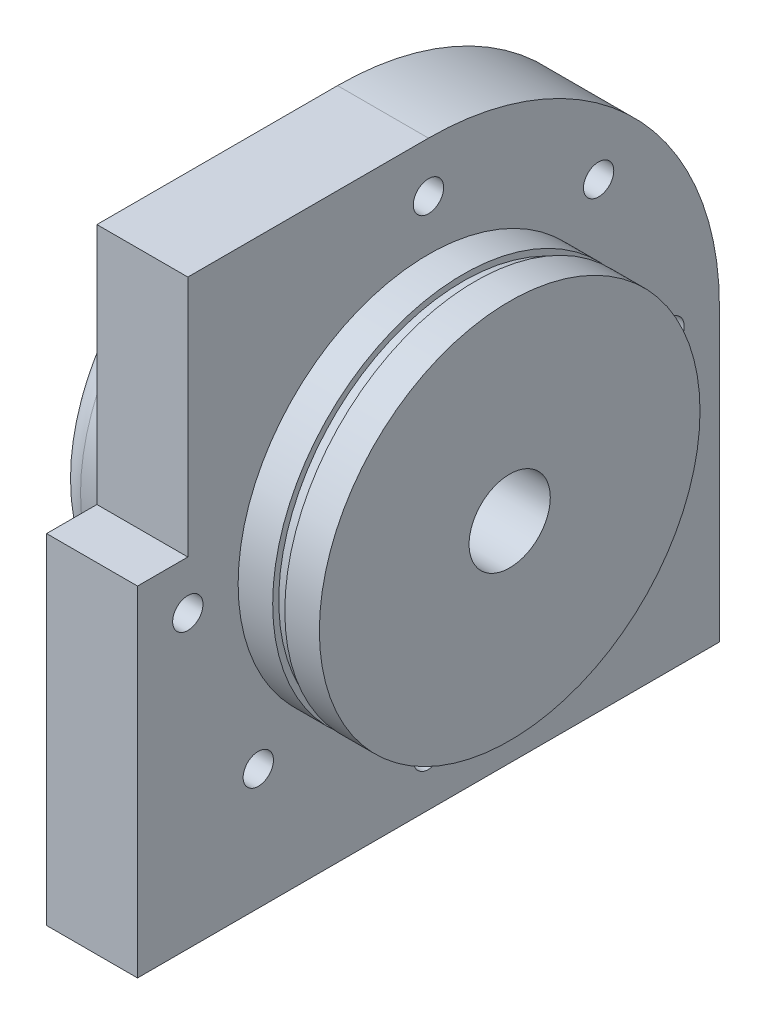
SolidWorks part; units mm, degrees
ref_plane "Front Plane" through (0, 0, 0) normal (0, 0, 1) x (1, 0, 0)
ref_plane "Top Plane" through (0, 0, 0) normal (0, 1, 0) x (1, 0, 0)
ref_plane "Right Plane" through (0, 0, 0) normal (1, 0, 0) x (0, 0, -1)
sketch "Sketch1" plane through (0, 0, 0) normal (1, 0, 0) x (0, 0, -1)
  circle A0 centre (0, 0) radius 39.878
extrude "Housing Fitting Extrude" add sketch "Sketch1" along normal blind 17.018
sketch "Sketch2" plane through (0, 0, 0) normal (-1, 0, 0) x (0, 0, 1)
  line L0 (60.96, 0) -> (60.96, 60.96)
  line L1 (60.96, 60.96) -> (0, 60.96)
  line L2 (60.96, 0) -> (60.96, -54.61)
  line L3 (60.96, -60.96) -> (-60.96, -60.96)
  line L7 (0, -9.3599) -> (0, 9.3599) construction
  line L11 (-60.96, 0) -> (-60.96, -54.61)
  line L12 (60.96, -60.96) -> (60.96, -54.61)
  line L13 (-60.96, -60.96) -> (-60.96, -54.61)
  arc A0 (0, 60.96) -> (-60.96, 0) centre (0, 0) ccw
extrude "Housing Body 1" add sketch "Sketch2" along normal blind 19.05 contours A0 L11 L13 L3 L12 L2 L0 L1
sketch "Sketch3" plane through (17.018, 0, 0) normal (1, 0, 0) x (0, 0, -1)
  circle A0 centre (0, 0) radius 8.509
extrude "Impeller Bore" cut sketch "Sketch3" against normal blind 17.018
sketch "Sketch4" plane through (0, 0, 0) normal (1, 0, 0) x (0, 0, -1)
  circle A0 centre (0, 0) radius 4
extrude "Shaft Bore" cut sketch "Sketch4" against normal blind 70.612
ref_plane "O-Ring Sketch Plane" through (8.509, 0, 0) normal (1, 0, 0) x (0, 0, -1)
sketch "Sketch5" plane through (8.509, 0, 0) normal (1, 0, 0) x (0, 0, -1)
  circle A0 centre (0, 0) radius 39.878
  circle A1 centre (0, 0) radius 38.608
extrude "O-Ring Cut" cut sketch "Sketch5" against normal blind 1.27 and the other way blind 1.27
sketch "Sketch7" plane through (-19.05, 0, 0) normal (-1, 0, 0) x (0, 0, 1)
  circle A0 centre (0, 0) radius 39.878
  circle A1 centre (0, 0) radius 4
extrude "Seal Side Body Ext" add sketch "Sketch7" along normal blind 19.05
fillet "Ext Fillet" radius 5.08 2 edges at (-38.1, 0, 39.878) (-19.05, 0, 39.878)
sketch "Sketch8" plane through (-19.05, 0, 0) normal (-1, 0, 0) x (0, 0, 1)
  circle A1 centre (52.959, 0) radius 3.175
extrude "Fastening Bore" [suppressed] cut sketch "Sketch8" against normal blind 19.05
pattern_circular "Fastening Bore Pattern" [suppressed] count 8 over 360
sketch "Sketch10" plane through (0, 0, 60.96) normal (0, 0, 1) x (1, 0, 0)
  line L0 (0, -60.96) -> (0, 60.96) construction
  line L1 (-19.05, 60.96) -> (0, 60.96)
  line L2 (-19.05, 60.96) -> (-19.05, 10.16)
  line L3 (-19.05, 10.16) -> (0, 10.16)
  line L4 (0, 60.96) -> (0, 10.16)
extrude "Discharge Cut" cut sketch "Sketch10" against normal blind 10.541
sketch "Sketch11" plane through (-38.1, 0, 0) normal (-1, 0, 0) x (0, 0, 1)
  circle A0 centre (0, 0) radius 19.05
extrude "Cut-Extrude1" cut sketch "Sketch11" against normal blind 27.94
sketch "Sketch12" plane through (0, 0, 0) normal (1, 0, 0) x (0, 0, -1)
  circle A0 centre (-50.419, 0) radius 3.175
extrude "Cut-Extrude2" cut sketch "Sketch12" against normal blind 19.05
pattern_circular "CirPattern1" count 8 over 360 about axis through (0, 0, 0) along (1, 0, 0) skipping 7 of "Cut-Extrude2"
